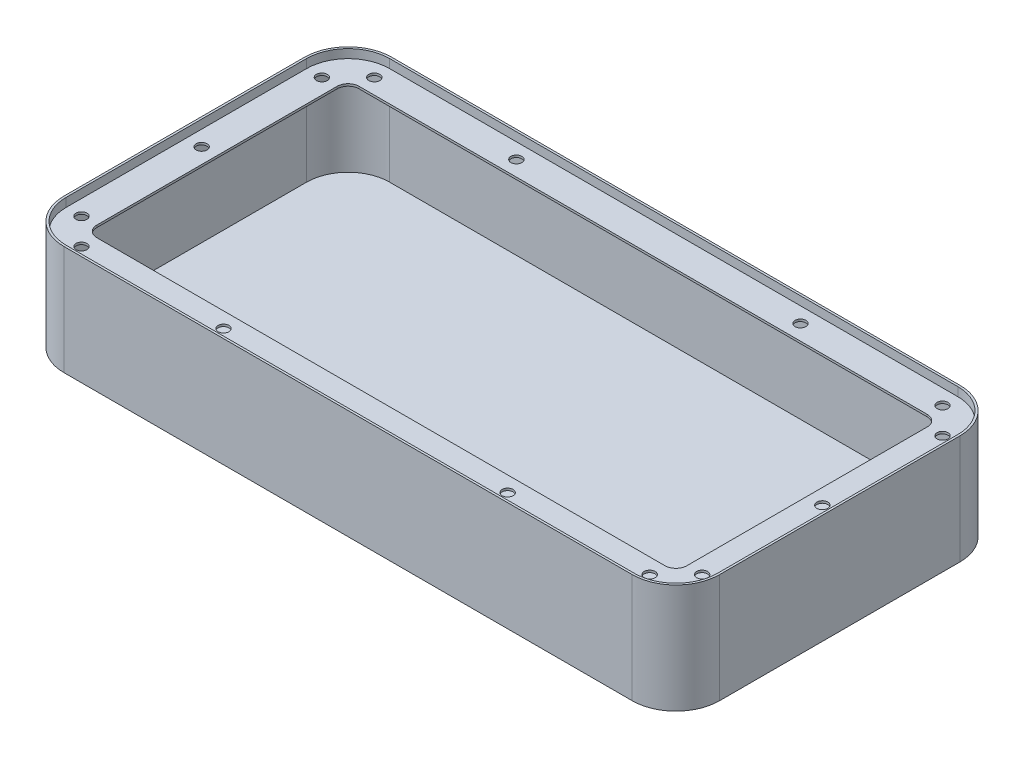
SolidWorks part; units mm, degrees
ref_plane "Front Plane" through (0, 0, 0) normal (0, 0, 1) x (1, 0, 0)
ref_plane "Top Plane" through (0, 0, 0) normal (0, 1, 0) x (1, 0, 0)
ref_plane "Right Plane" through (0, 0, 0) normal (1, 0, 0) x (0, 0, -1)
sketch "Sketch1" plane through (0, 0, 0) normal (0, 1, 0) x (1, 0, 0)
  line L1 (-130, -75) -> (130, -75)
  line L2 (-150, -55) -> (-150, 55)
  line L3 (-130, 75) -> (130, 75)
  line L4 (150, -55) -> (150, 55)
  line L5 (-150, -75) -> (150, 75) construction
  line L6 (-150, 75) -> (150, -75) construction
  arc A0 (130, 75) -> (150, 55) centre (130, 55) cw
  arc A1 (130, -75) -> (150, -55) centre (130, -55) ccw
  arc A2 (-130, -75) -> (-150, -55) centre (-130, -55) cw
  arc A3 (-150, 55) -> (-130, 75) centre (-130, 55) cw
  point P0 (0, 0)
  dimension "D3" = 20
  dimension "D1" = 300
  dimension "D2" = 150
extrude "Boss-Extrude1" add sketch "Sketch1" along normal blind 50
shell "Shell1" thickness 1
sketch "Sketch3" plane through (0, 50, 0) normal (0, -1, 0) x (-1, 0, 0)
  line L0 (130, -60) -> (-130, -60)
  line L1 (130, 75) -> (-130, 75)
  line L2 (150, 55) -> (150, -55)
  line L3 (130, -75) -> (-130, -75)
  line L4 (-150, 55) -> (-150, -55)
  line L5 (150, 75) -> (-150, -75) construction
  line L6 (150, -75) -> (-150, 75) construction
  line L7 (-135, 55) -> (-135, -55)
  line L8 (130, 60) -> (-130, 60)
  line L9 (135, 55) -> (135, -55)
  arc A0 (130, 75) -> (150, 55) centre (130, 55) cw
  arc A1 (-150, 55) -> (-130, 75) centre (-130, 55) cw
  arc A2 (-150, -55) -> (-130, -75) centre (-130, -55) ccw
  arc A3 (150, -55) -> (130, -75) centre (130, -55) cw
  arc A4 (-135, -55) -> (-130, -60) centre (-130, -55) ccw
  arc A5 (-135, 55) -> (-130, 60) centre (-130, 55) cw
  arc A6 (130, 60) -> (135, 55) centre (130, 55) cw
  arc A7 (135, -55) -> (130, -60) centre (130, -55) cw
  point P0 (0, 0)
  dimension "D3" = 20
  dimension "D1" = 300
  dimension "D2" = 150
  dimension "D4" = 15
extrude "Boss-Extrude3" add sketch "Sketch3" along normal blind 1 from offset 4
sketch "Sketch4" plane through (0, 46, 0) normal (0, 1, 0) x (1, 0, 0)
  line L1 (-130, -67) -> (-130, -74) construction
  line L2 (130, -67) -> (130, -74) construction
  line L3 (-130, 67) -> (130, 67) construction
  line L4 (-130, -67) -> (130, -67) construction
  line L5 (130, 67) -> (130, 74) construction
  line L8 (-149, -55) -> (-142, -55) construction
  line L10 (-149, 55) -> (-142, 55) construction
  line L11 (-142, 55) -> (-142, -55) construction
  line L13 (149, -55) -> (149, 55) construction
  line L14 (149, -55) -> (142, -55) construction
  line L16 (149, 55) -> (142, 55) construction
  line L17 (142, 55) -> (142, -55) construction
  line L18 (-130, 67) -> (-65, 67) construction
  line L19 (130, 67) -> (65, 67) construction
  line L20 (-130, -67) -> (-65, -67) construction
  line L21 (130, -67) -> (65, -67) construction
  arc A0 (130, -74) -> (149, -55) centre (130, -55) ccw construction
  dimension "D1" = 65
  dimension "D2" = 65
  dimension "D3" = 7
  dimension "D4" = 7
  dimension "D5" = 7
  dimension "D6" = 7
hole_wizard "Ø5.0mm Dowel Hole2" positions "Sketch8" profile "Sketch9" hole size "Ø5.0" standard "AS"
sketch "Sketch8" plane through (0, 46, 0) normal (0, 1, 0) x (1, 0, 0)
  line L0 (142, 55) -> (142, -55) construction
  line L1 (-142, 55) -> (-142, -55) construction
  point P0 (-65, 67)
  point P3 (65, 67)
  point P6 (142, 0)
  point P10 (-142, 0)
  point P14 (-65, -67)
  point P17 (65, -67)
sketch "Sketch9" plane through (-65, 46, -67) normal (1, 0, 0) x (0, 0, 1)
  line L0 (0, 0) -> (0, 1)
  line L1 (0, 1) -> (2.5, 1)
  line L2 (2.5, 1) -> (2.5, 0)
  line L5 (2.5, 0) -> (0, 0)
  line L11 (0, -6.35) -> (0, 107.95) construction
  dimension "Thru Hole Dia." = 5
  dimension "Thru Hole Depth" = 1
hole_wizard "Ø5.0mm Dowel Hole3" positions "Sketch10" profile "Sketch11" hole size "Ø5.0" standard "AS"
sketch "Sketch10" plane through (0, 46, 0) normal (0, 1, 0) x (1, 0, 0)
  point P0 (-130, 67)
  point P3 (-142, 55)
  point P6 (-142, -55)
  point P9 (-130, -67)
  point P12 (130, -67)
  point P15 (142, -55)
  point P18 (142, 55)
  point P21 (130, 67)
sketch "Sketch11" plane through (-130, 46, -67) normal (1, 0, 0) x (0, 0, 1)
  line L0 (0, 0) -> (0, 1)
  line L1 (0, 1) -> (2.5, 1)
  line L2 (2.5, 1) -> (2.5, 0)
  line L5 (2.5, 0) -> (0, 0)
  line L11 (0, -6.35) -> (0, 107.95) construction
  dimension "Thru Hole Dia." = 5
  dimension "Thru Hole Depth" = 1
